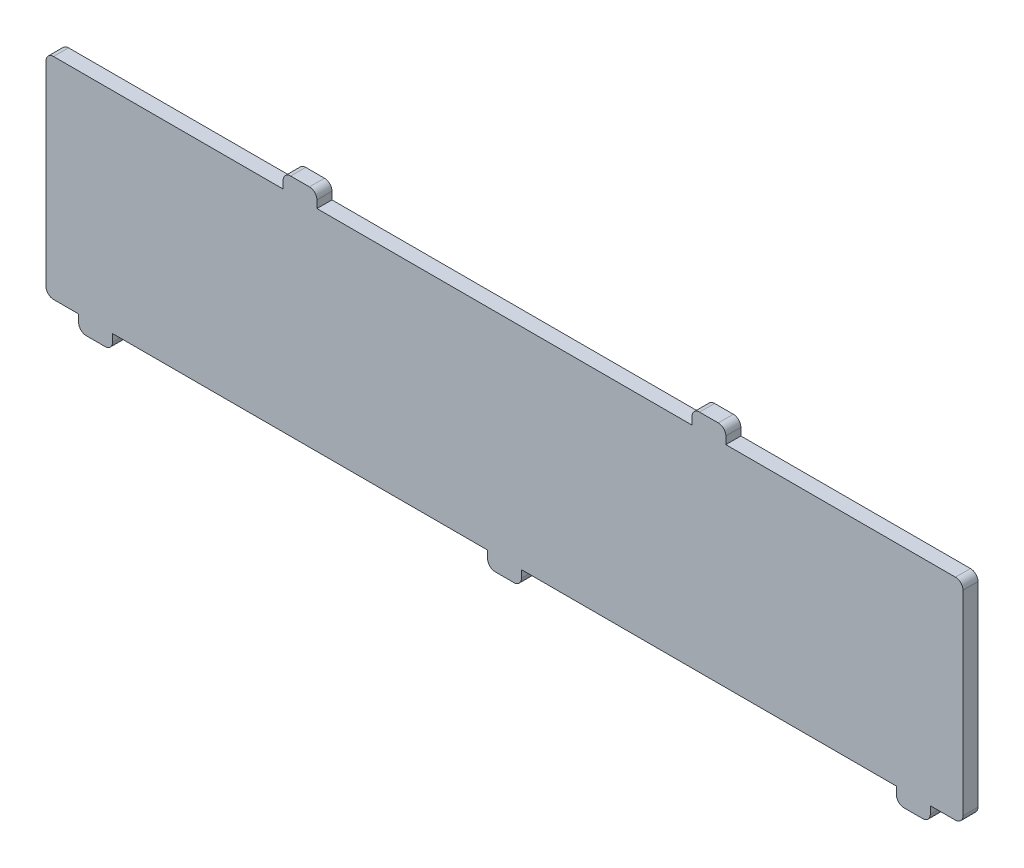
SolidWorks part; units mm, degrees
ref_plane "前基準面" through (0, 0, 0) normal (0, 0, 1) x (1, 0, 0)
ref_plane "上基準面" through (0, 0, 0) normal (0, 1, 0) x (1, 0, 0)
ref_plane "右基準面" through (0, 0, 0) normal (1, 0, 0) x (0, 0, -1)
sketch "Sketch1" plane through (0, 0, 0) normal (0, 0, 1) x (1, 0, 0)
  line L0 (0, 0) -> (0, -31.2064) construction
  line L1 (-61, 14) -> (61, 14)
  line L2 (-61, 14) -> (-61, -14)
  line L3 (-61, -14) -> (61, -14)
  line L4 (61, 14) -> (61, -14)
  line L5 (-61, 14) -> (61, -14) construction
  line L6 (-61, -14) -> (61, 14) construction
  line L7 (0, -31.2064) -> (0, 29.4941) construction
  line L8 (-2.25, -14) -> (2.25, -16) construction
  line L9 (-2.25, -14) -> (2.25, -14)
  line L10 (-2.25, -14) -> (-2.25, -16)
  line L11 (-2.25, -16) -> (2.25, -16)
  line L12 (2.25, -14) -> (2.25, -16)
  line L13 (-2.25, -16) -> (2.25, -14) construction
  line L14 (-56.65, -14) -> (-52.15, -16) construction
  line L15 (-56.65, -14) -> (-52.15, -14)
  line L16 (-56.65, -14) -> (-56.65, -16)
  line L17 (-56.65, -16) -> (-52.15, -16)
  line L18 (-52.15, -14) -> (-52.15, -16)
  line L19 (-52.15, -14) -> (-56.65, -16) construction
  line L20 (56.65, -16) -> (52.15, -16)
  line L21 (52.15, -14) -> (52.15, -16)
  line L22 (56.65, -14) -> (52.15, -14)
  line L23 (56.65, -14) -> (56.65, -16)
  line L24 (-54.4, -15) -> (-54.4, 18.4346) construction
  line L25 (0, -15.6032) -> (0, 17.9346) construction
  line L26 (52.15, -14) -> (56.65, -16) construction
  line L27 (56.65, -14) -> (52.15, -16) construction
  line L28 (-29.45, 16) -> (-24.95, 14) construction
  line L29 (-29.45, 14) -> (-24.95, 14)
  line L30 (-29.45, 14) -> (-29.45, 16)
  line L31 (-29.45, 16) -> (-24.95, 16)
  line L32 (-24.95, 14) -> (-24.95, 16)
  line L33 (-24.95, 16) -> (-29.45, 14) construction
  line L34 (29.45, 16) -> (24.95, 16)
  line L35 (24.95, 14) -> (24.95, 16)
  line L36 (29.45, 14) -> (24.95, 14)
  line L37 (29.45, 14) -> (29.45, 16)
  point P0 (0, 0)
  point P13 (0, -15)
  point P18 (-54.4, -15)
  point P19 (0, -15.6032)
  point P32 (-27.2, 15)
  dimension "D1" = 28
  dimension "D2" = 122
  dimension "D3" = 2
  dimension "D4" = 4.5
  dimension "D5" = 2
  dimension "D6" = 4.5
  dimension "D7" = 54.4
  dimension "D8" = 2
  dimension "D9" = 4.5
  dimension "D10" = 27.2
extrude "Boss-Extrude1" add sketch "Sketch1" along normal mid plane 2 contours L4 L1 L2 L3 | L12 L3 L10 L11 | L1 L37 L34 L35 | L1 L32 L31 L30 | L18 L17 L16 L15 | L23 L20 L21 L22
fillet "Fillet1" radius 1 14 edges at (61, -14, 0) (2.25, -16, 0) (-2.25, -16, 0) (-61, -14, 0) (-61, 14, 0) (-29.45, 16, 0) (-24.95, 16, 0) (24.95, 16, 0) (29.45, 16, 0) (61, 14, 0) (-56.65, -16, 0) (-52.15, -16, 0) (52.15, -16, 0) (56.65, -16, 0)
